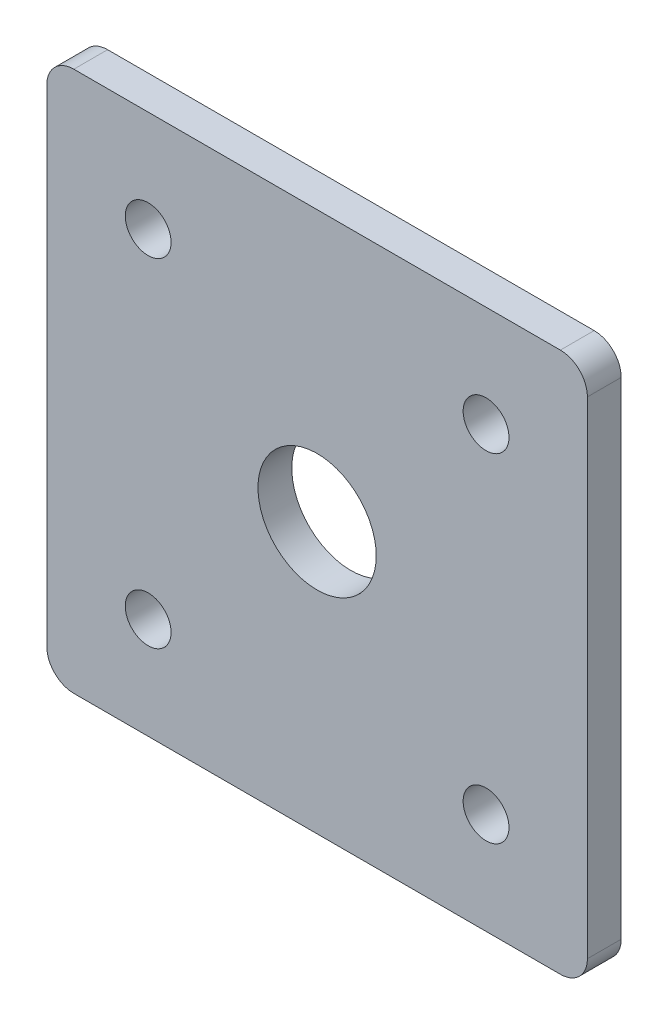
SolidWorks part; units mm, degrees
ref_plane "Front Plane" through (0, 0, 0) normal (0, 0, 1) x (1, 0, 0)
ref_plane "Top Plane" through (0, 0, 0) normal (0, 1, 0) x (1, 0, 0)
ref_plane "Right Plane" through (0, 0, 0) normal (1, 0, 0) x (0, 0, -1)
sketch "Sketch1" plane through (0, 0, 0) normal (0, 0, 1) x (1, 0, 0)
  line L1 (-25.4, -25.4) -> (25.4, -25.4)
  line L2 (-25.4, -25.4) -> (-25.4, 25.4)
  line L3 (-25.4, 25.4) -> (25.4, 25.4)
  line L4 (25.4, -25.4) -> (25.4, 25.4)
  line L5 (-25.4, -25.4) -> (25.4, 25.4) construction
  line L6 (-25.4, 25.4) -> (25.4, -25.4) construction
  circle A0 centre (0, 0) radius 5.5562
  point P0 (0, 0)
  dimension "D3" = 11.1125
  dimension "D1" = 50.8
extrude "Boss-Extrude1" add sketch "Sketch1" against normal mid plane 3.175
hole_wizard "#8 Clearance Hole1" positions "Sketch3" profile "Sketch2" hole size "#8" standard "ANSI Inch" end condition through all
sketch "Sketch3" plane through (0, 0, 1.5875) normal (0, 0, 1) x (1, 0, 0)
  line L1 (-15.875, -15.875) -> (15.875, -15.875) construction
  line L2 (-15.875, -15.875) -> (-15.875, 15.875) construction
  line L3 (-15.875, 15.875) -> (15.875, 15.875) construction
  line L4 (15.875, -15.875) -> (15.875, 15.875) construction
  line L5 (-15.875, -15.875) -> (15.875, 15.875) construction
  line L6 (-15.875, 15.875) -> (15.875, -15.875) construction
  line L7 (-25.4, 25.4) -> (-25.4, -25.4) construction
  point P0 (-15.875, 15.875)
  point P2 (15.875, 15.875)
  point P4 (15.875, -15.875)
  point P6 (-15.875, -15.875)
  point P7 (0, 0)
  dimension "D1" = 9.525
sketch "Sketch2" plane through (-15.875, 15.875, 1.5875) normal (1, 0, 0) x (0, -1, 0)
  line L0 (0, 0) -> (0, 3.175)
  line L1 (0, 3.175) -> (2.1526, 3.175)
  line L2 (2.1526, 3.175) -> (2.1526, 0)
  line L5 (2.1526, 0) -> (0, 0)
  line L11 (0, -6.35) -> (0, 107.95) construction
  dimension "Thru Hole Dia." = 4.3053
  dimension "Thru Hole Depth" = 3.175
fillet "Fillet1" radius 2.54 4 edges at (-25.4, -25.4, 0) (25.4, -25.4, 0) (25.4, 25.4, 0) (-25.4, 25.4, 0)
